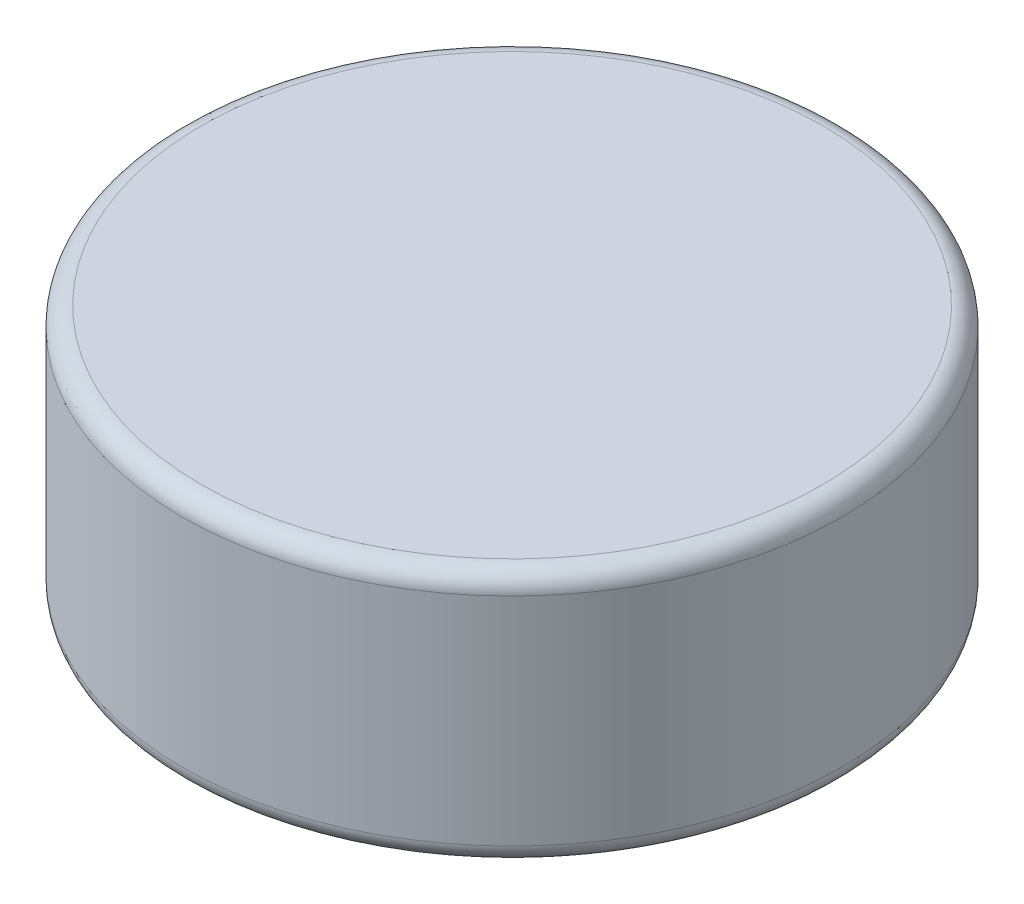
SolidWorks part; units mm, degrees
ref_plane "Plano frontal" through (0, 0, 0) normal (0, 0, 1) x (1, 0, 0)
ref_plane "Plano superior" through (0, 0, 0) normal (0, 1, 0) x (1, 0, 0)
ref_plane "Plano direito" through (0, 0, 0) normal (1, 0, 0) x (0, 0, -1)
sketch "Esboço1" plane through (0, 0, 0) normal (0, 1, 0) x (1, 0, 0)
  circle A0 centre (0, 0) radius 35
  dimension "D1" = 70
extrude "Ressalto-extrusão1" add sketch "Esboço1" along normal blind 27
fillet "Filete1" radius 2 2 edges at (0, 0, 35) (0, 27, 35)
sketch "Esboço2" plane through (0, 0, 0) normal (0, -1, 0) x (-1, 0, 0)
  circle A0 centre (0, 0) radius 5.75
  dimension "D1" = 11.5
extrude "Ressalto-extrusão2" add sketch "Esboço2" along normal blind 2
sketch "Esboço3" plane through (0, -2, 0) normal (0, -1, 0) x (1, 0, 0)
  circle A0 centre (0, 0) radius 3
  dimension "D1" = 6
extrude "Corte-extrusão1" cut sketch "Esboço3" against normal blind 5
